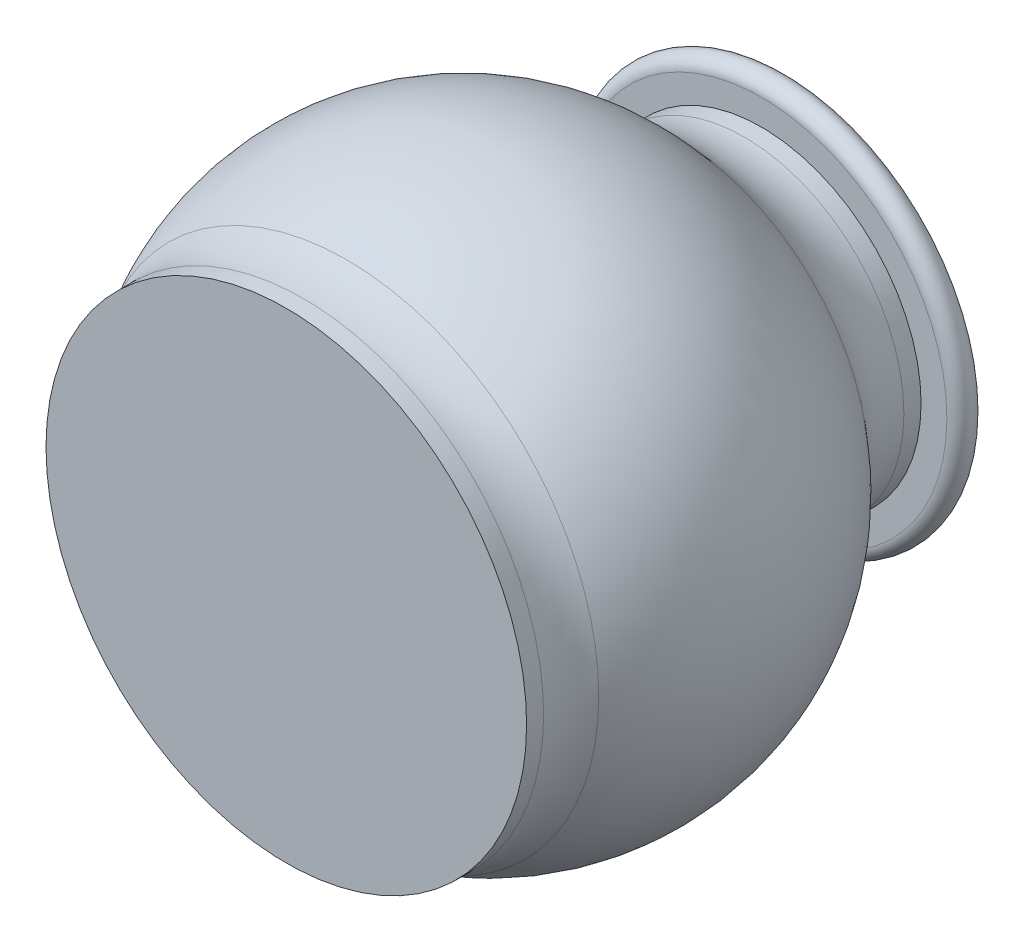
SolidWorks part; units mm, degrees
ref_plane "Front Plane" through (0, 0, 0) normal (0, 0, 1) x (1, 0, 0)
ref_plane "Top Plane" through (0, 0, 0) normal (0, 1, 0) x (1, 0, 0)
ref_plane "Right Plane" through (0, 0, 0) normal (1, 0, 0) x (0, 0, -1)
sketch "Sketch1" plane through (0, 0, 0) normal (0, 1, 0) x (1, 0, 0)
  line L0 (0, 0) -> (-27.9599, 0)
  line L1 (-27.9599, 0) -> (-27.9599, 1.9791)
  line L2 (-18.5836, 53.2737) -> (-18.5836, 55.2737)
  line L3 (-18.5836, 55.2737) -> (-21.5836, 55.2737)
  line L4 (0, 3) -> (-25, 3)
  line L5 (-25, 3) -> (-25, 3)
  line L6 (-15.5836, 53.2737) -> (-15.5836, 58.2737)
  line L7 (-15.5836, 58.2737) -> (-21.5836, 58.2737)
  line L8 (0, 0) -> (0, 90.4801) construction
  line L9 (0, 0) -> (0, 3)
  arc A0 (-29.3276, 7.0272) -> (-22.2954, 45.4982) centre (-3.4308, 22.1717) cw
  arc A1 (-18.5836, 53.2737) -> (-22.2954, 45.4982) centre (-28.5836, 53.2737) cw
  arc A2 (-29.3276, 7.0272) -> (-27.9599, 1.9791) centre (-37.9599, 1.9791) cw
  arc A3 (-26.7379, 8.5417) -> (-25, 3) centre (-37.9599, 1.9791) cw
  arc A4 (-26.7379, 8.5417) -> (-20.4089, 43.1655) centre (-3.4308, 22.1717) cw
  arc A5 (-15.5836, 53.2737) -> (-20.4089, 43.1655) centre (-28.5836, 53.2737) cw
  arc A6 (-21.5836, 58.2737) -> (-21.5836, 55.2737) centre (-21.5836, 56.7737) ccw
  dimension "D1" = 10
  dimension "D2" = 10
  dimension "D7" = 30
  dimension "D4" = 25
  dimension "D5" = 6
  dimension "D6" = 5
  dimension "D3" = 3
revolve "Revolve1" add sketch "Sketch1" angle 360 about L8
